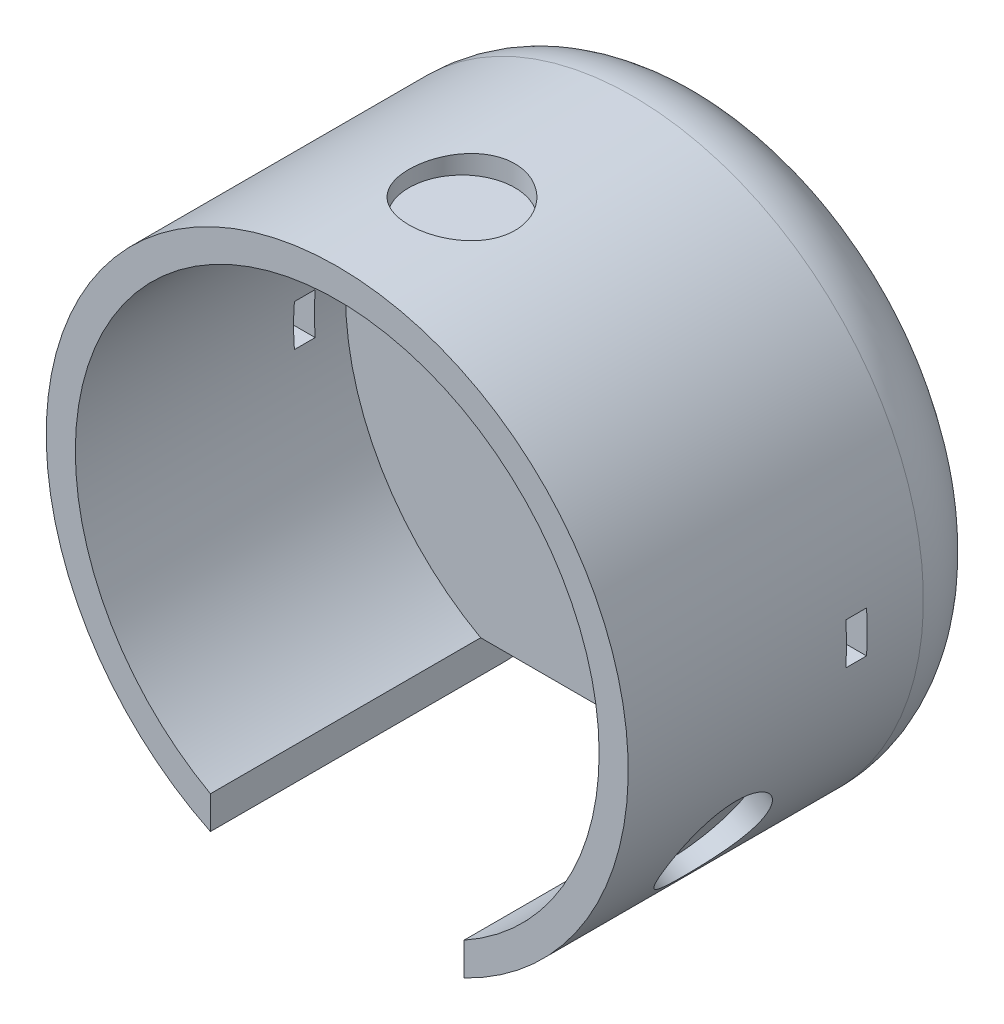
SolidWorks part; units mm, degrees
ref_plane "Front Plane" through (0, 0, 0) normal (0, 0, 1) x (1, 0, 0)
ref_plane "Top Plane" through (0, 0, 0) normal (0, 1, 0) x (1, 0, 0)
ref_plane "Right Plane" through (0, 0, 0) normal (1, 0, 0) x (0, 0, -1)
sketch "Sketch1" plane through (0, 0, 0) normal (0, 0, 1) x (1, 0, 0)
  circle A0 centre (0, 0) radius 17.78
  circle A1 centre (0, 0) radius 16.002
  dimension "D1" = 35.56
  dimension "D2" = 32.004
extrude "Boss-Extrude1" add sketch "Sketch1" along normal blind 16.51
sketch "Sketch2" plane through (0, 0, 0) normal (0, 0, -1) x (-1, 0, 0)
  circle A0 centre (0, 0) radius 17.78
extrude "Boss-Extrude2" add sketch "Sketch2" along normal blind 6.604
fillet "Fillet1" radius 5.08 1 edges at (-17.78, 0, -6.604)
ref_plane "Plane4" through (0, 17.78, 0) normal (0, 1, 0) x (1, 0, 0)
sketch "Sketch3" plane through (0, 17.78, 0) normal (0, 1, 0) x (1, 0, 0)
  line L0 (-17.78, -16.51) -> (17.78, -16.51) construction
  circle A0 centre (0, -8.89) radius 3.2385
  dimension "D2" = 6.477
  dimension "D1" = 7.62
extrude "Cut-Extrude1" cut sketch "Sketch3" against normal blind 1.27
pattern_circular "CirPattern1" count 3 over 360 about axis through (0, 0, 0) along (0, 0, 1) of "Cut-Extrude1"
sketch "Sketch4" plane through (0, 0, 16.51) normal (0, 0, 1) x (1, 0, 0)
  line L0 (0, -0.4039) -> (0, -11.7743) construction
  line L1 (-7.747, 14.0017) -> (7.747, 14.0017)
  line L2 (-7.747, 14.0017) -> (-7.747, 19.1752)
  line L3 (-7.747, 19.1752) -> (7.747, 19.1752)
  line L4 (7.747, 14.0017) -> (7.747, 19.1752)
  circle A0 centre (0, 0) radius 16.002 construction
  dimension "D1" = 15.494
  dimension "D2" = 7.747
extrude "Cut-Extrude2" [suppressed] cut sketch "Sketch4" against normal up to surface (16.51 mm away)
sketch "Sketch5" [suppressed] plane through (0, 0, 0) normal (0, 0, 1) x (1, 0, 0)
  line L0 (-7.747, 16.0035) -> (7.747, 16.0035)
  arc A0 (-7.747, 16.0035) -> (7.747, 16.0035) centre (0, 0) cw
extrude "Cut-Extrude3" [suppressed] cut sketch "Sketch5" against normal through all
sketch "Sketch6" plane through (0, 0, 16.51) normal (0, 0, 1) x (1, 0, 0)
  line L2 (-7.747, -16.0035) -> (-7.747, -14.0017)
  line L3 (-7.747, -14.0017) -> (7.747, -14.0017)
  line L4 (7.747, -16.0035) -> (7.747, -14.0017)
  circle A0 centre (0, 0) radius 17.78 construction
  circle A1 centre (0, 0) radius 16.002 construction
  arc A2 (-7.747, -16.0035) -> (7.747, -16.0035) centre (0, 0) ccw
  dimension "D1" = 15.494
  dimension "D2" = 7.747
extrude "Cut-Extrude4" cut sketch "Sketch6" against normal through all
ref_plane "Plane5" through (17.78, 0, 0) normal (1, 0, 0) x (0, 0, -1)
sketch "Sketch7" plane through (17.78, 0, 0) normal (1, 0, 0) x (0, 0, -1)
  line L0 (1.524, 17.78) -> (1.524, -16.0035) construction
  line L1 (-3.175, -1.27) -> (-1.905, -1.27)
  line L2 (-3.175, -1.27) -> (-3.175, 1.27)
  line L3 (-3.175, 1.27) -> (-1.905, 1.27)
  line L4 (-1.905, -1.27) -> (-1.905, 1.27)
  line L5 (-3.175, -1.27) -> (-1.905, 1.27) construction
  line L6 (-3.175, 1.27) -> (-1.905, -1.27) construction
  point P0 (-2.54, 0)
  dimension "D1" = 1.27
  dimension "D2" = 2.54
  dimension "D3" = 3.429
extrude "Cut-Extrude5" cut sketch "Sketch7" against normal through all
